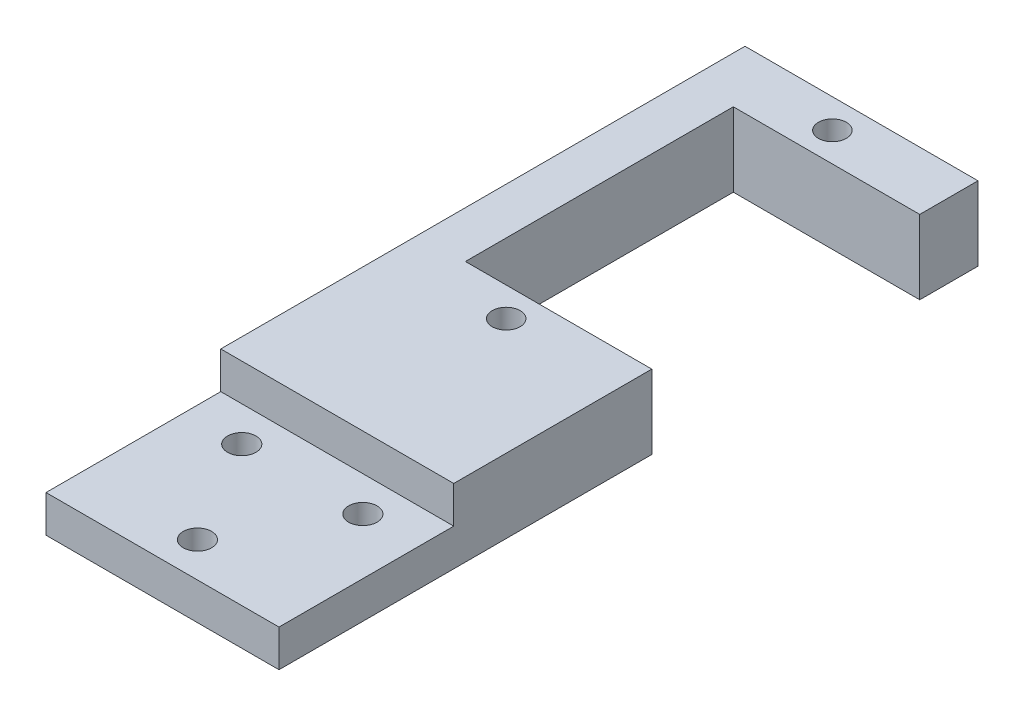
SolidWorks part; units mm, degrees
material "ABS"
ref_plane "Front" through (0, 0, 0) normal (0, 0, 1) x (1, 0, 0)
ref_plane "Top" through (0, 0, 0) normal (0, 1, 0) x (1, 0, 0)
ref_plane "Right" through (0, 0, 0) normal (1, 0, 0) x (0, 0, -1)
sketch "Sketch2" plane through (0, 0, 0) normal (0, 1, 0) x (1, 0, 0)
  line L1 (0, 0) -> (20, 0)
  line L2 (0, 0) -> (0, -60)
  line L3 (0, -60) -> (20, -60)
  line L4 (20, 0) -> (20, -60)
  dimension "D1" = 20
  dimension "D2" = 60
extrude "Boss-Extrude1" add sketch "Sketch2" along normal blind 6.35
sketch "Sketch4" plane through (0, 6.35, 0) normal (0, 1, 0) x (1, 0, 0)
  line L1 (4, -5) -> (20, -5)
  line L2 (4, -5) -> (4, -28)
  line L3 (4, -28) -> (20, -28)
  line L4 (20, -5) -> (20, -28)
  line L6 (20, 0) -> (0, 0) construction
  line L8 (0, 0) -> (0, -60) construction
  line L9 (20, -60) -> (20, 0) construction
  dimension "D1" = 4
  dimension "D2" = 5
  dimension "D3" = 23
extrude "Cut-Extrude1" cut sketch "Sketch4" against normal through all
hole_wizard "M2 Clearance Hole1" positions "Sketch8" profile "Sketch9" hole size "M2" standard "IS" end condition through all
sketch "Sketch8" plane through (0, 6.35, 0) normal (0, 1, 0) x (1, 0, 0)
  line L0 (10, 0) -> (10, -60) construction
  line L1 (20, 0) -> (0, 0) construction
  line L2 (0, -60) -> (20, -60) construction
  line L3 (4, -28) -> (20, -28) construction
  point P9 (10, -2.5)
  point P11 (10, -30.5)
  dimension "D1" = 2.5
  dimension "D2" = 2.5
sketch "Sketch9" plane through (10, 6.35, 30.5) normal (1, 0, 0) x (0, 0, 1)
  line L0 (0, 0) -> (0, 6.35)
  line L1 (0, 6.35) -> (1.2, 6.35)
  line L2 (1.2, 6.35) -> (1.2, 0)
  line L5 (1.2, 0) -> (0, 0)
  line L11 (0, -6.35) -> (0, 107.95) construction
  dimension "Thru Hole Dia." = 2.4
  dimension "Thru Hole Depth" = 6.35
sketch "Sketch10" plane through (20, 0, 0) normal (1, 0, 0) x (0, 0, -1)
  line L0 (-60, 6.35) -> (-60, 0) construction
  line L1 (-60, 6.35) -> (-45, 6.35)
  line L2 (-60, 6.35) -> (-60, 3.175)
  line L3 (-60, 3.175) -> (-45, 3.175)
  line L4 (-45, 6.35) -> (-45, 3.175)
  dimension "D1" = 15
extrude "Cut-Extrude2" cut sketch "Sketch10" against normal through all
sketch "Sketch12" plane through (0, 3.175, 0) normal (0, 1, 0) x (1, 0, 0)
  line L0 (10, -60) -> (10, -45) construction
  line L1 (0, -60) -> (20, -60) construction
  line L2 (0, -45) -> (20, -45) construction
  line L3 (10, -57) -> (15.1962, -48) construction
  line L4 (15.1962, -48) -> (4.8038, -48) construction
  line L5 (4.8038, -48) -> (10, -57) construction
  dimension "D1" = 9
  dimension "D2" = 3
hole_wizard "#2 Clearance Hole1" positions "Sketch13" profile "Sketch14" hole size "#2" standard "ANSI Inch" end condition through all
sketch "Sketch13" plane through (0, 3.175, 0) normal (0, 1, 0) x (1, 0, 0)
  point P9 (4.8038, -48)
  point P12 (15.1962, -48)
  point P15 (10, -57)
sketch "Sketch14" plane through (4.8038, 3.175, 48) normal (1, 0, 0) x (0, 0, 1)
  line L0 (0, 0) -> (0, 3.175)
  line L1 (0, 3.175) -> (1.2192, 3.175)
  line L2 (1.2192, 3.175) -> (1.2192, 0)
  line L5 (1.2192, 0) -> (0, 0)
  line L11 (0, -6.35) -> (0, 107.95) construction
  dimension "Thru Hole Dia." = 2.4384
  dimension "Thru Hole Depth" = 3.175
